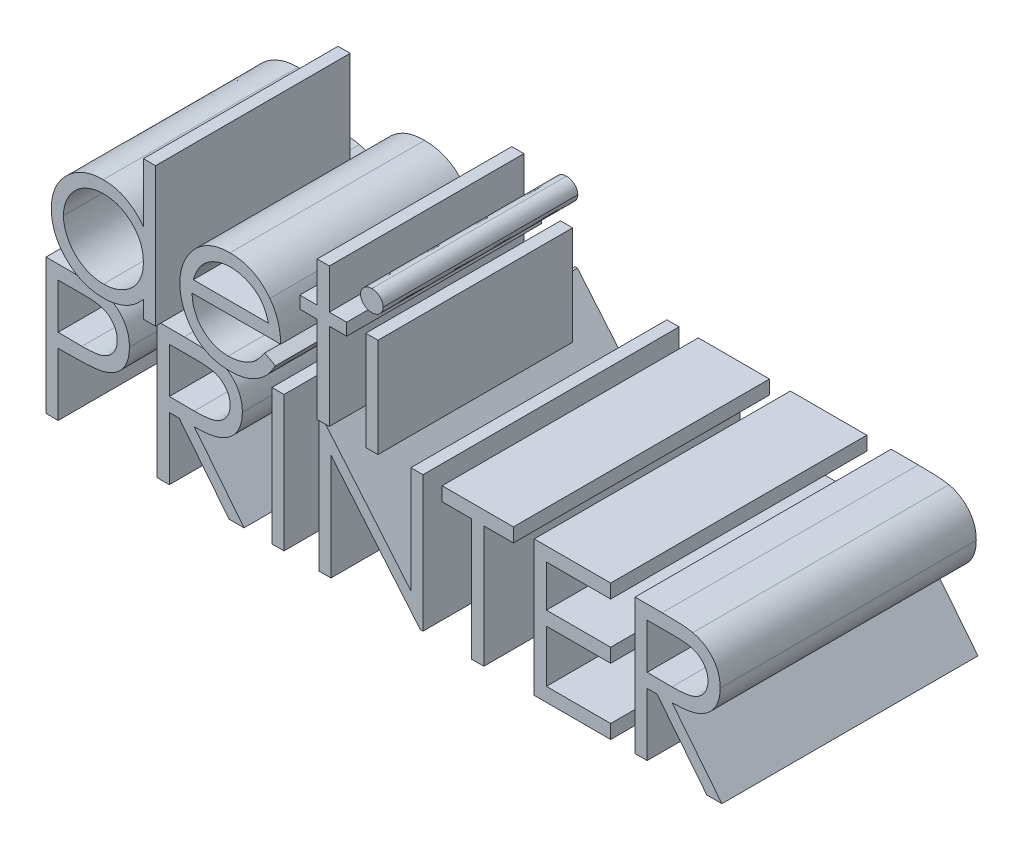
SolidWorks part; units mm, degrees
ref_plane "Front Plane" through (0, 0, 0) normal (0, 0, 1) x (1, 0, 0)
ref_plane "Top Plane" through (0, 0, 0) normal (0, 1, 0) x (1, 0, 0)
ref_plane "Right Plane" through (0, 0, 0) normal (1, 0, 0) x (0, 0, -1)
sketch "Sketch1" plane through (0, 0, 0) normal (0, 0, 1) x (1, 0, 0)
  line L0 (0, 0) -> (150, 0) construction
  text T0 "PRINTER" font "Century Gothic" height in points 100
  dimension "D1" = 150
extrude "Boss-Extrude1" add sketch "Sketch1" along normal blind 50
sketch "Sketch2" plane through (0, 0, 50) normal (0, 0, 1) x (1, 0, 0)
  line L0 (3.3921, 26.4583) -> (123.6789, 26.4583) construction
  text T0 "deti" font "Century Gothic" height in points 100
extrude "Boss-Extrude2" add sketch "Sketch2" against normal offset from surface 37 and the other way blind 1 up to face at (9.2994, 15.8368, 50)
